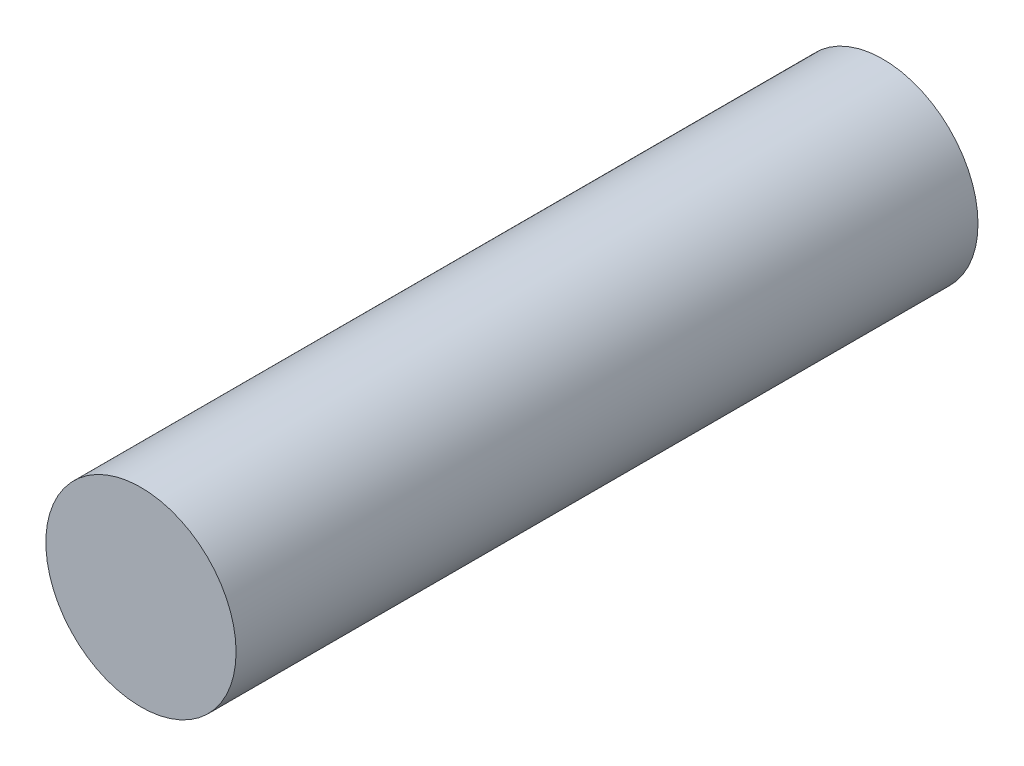
SolidWorks part; units mm, degrees
ref_plane "Plan1" through (0, 0, 0) normal (0, 0, 1) x (1, 0, 0)
ref_plane "Plan2" through (0, 0, 0) normal (0, 1, 0) x (1, 0, 0)
ref_plane "Plan3" through (0, 0, 0) normal (1, 0, 0) x (0, 0, -1)
ref_plane "Plan4" through (0, 0, 7.1949) normal (0, 0, 1) x (1, 0, 0)
sketch "section-aiguille" plane through (0, 0, 7.1949) normal (0, 0, 1) x (1, 0, 0)
  line L0 (11.1227, 7.3603) -> (11.1227, -6.6397) construction
  circle A0 centre (11.1227, -5.7312) radius 1
  circle A1 centre (11.1227, 0.3603) radius 5.0915 construction
  dimension "D1" = 2
extrude "aiguille" add sketch "section-aiguille" against normal blind 7.8
